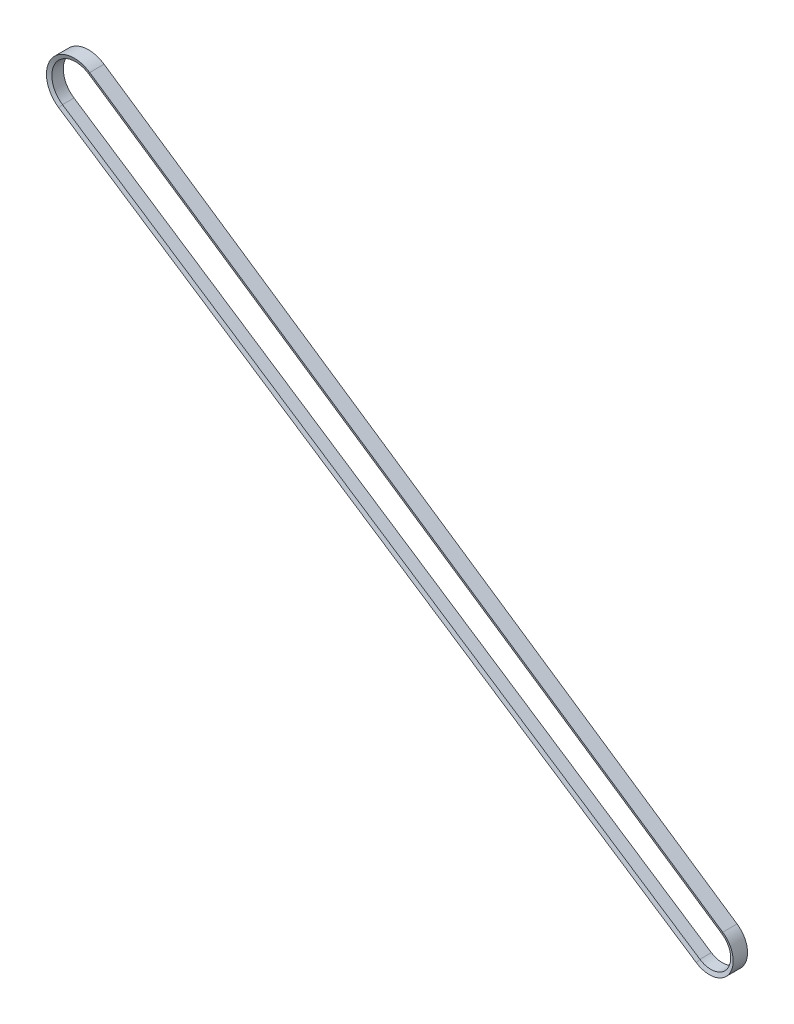
SolidWorks part; units mm, degrees
ref_plane "前视基准面" through (0, 0, 0) normal (0, 0, 1) x (1, 0, 0)
ref_plane "上视基准面" through (0, 0, 0) normal (0, 1, 0) x (1, 0, 0)
ref_plane "右视基准面" through (0, 0, 0) normal (1, 0, 0) x (0, 0, -1)
sketch "草图2" plane through (0, 0, 0) normal (0, 0, 1) x (1, 0, 0)
  line L0 (0, 0) -> (1, 0) construction
  line L1 (0, 0) -> (0, 1) construction
  line L4 (166.6723, -117.8278) -> (-3.5036, -5.2984)
  line L5 (3.558, 5.262) -> (172.5644, -109.0164)
  arc A1 (172.5644, -109.0164) -> (166.6723, -117.8278) centre (169.5956, -113.4069) cw
  arc A2 (-3.5036, -5.2984) -> (3.558, 5.262) centre (0, 0) cw
ref_plane "基准面4" through (172.5644, -109.0164, 0) normal (0.8284, -0.5601, 0) x (0, 0, -1)
sketch "草图4" plane through (172.5644, -109.0164, 0) normal (0.8284, -0.5601, 0) x (0, 0, -1)
  line L7 (-1.535, 0) -> (1.535, 0)
  line L8 (0, 0) -> (0, -10.5997) construction
  line L9 (0, 0) -> (0, -10.6) construction
  line L10 (1.535, 0) -> (1.9179, 1.052)
  line L11 (1.9179, 1.052) -> (-1.9179, 1.052)
  line L12 (0, 1.052) -> (0, 0)
  line L13 (-1.535, 0) -> (-1.9179, 1.052)
  dimension "D1" = 110
sweep "扫描2" add profiles "草图4" path "草图2"
